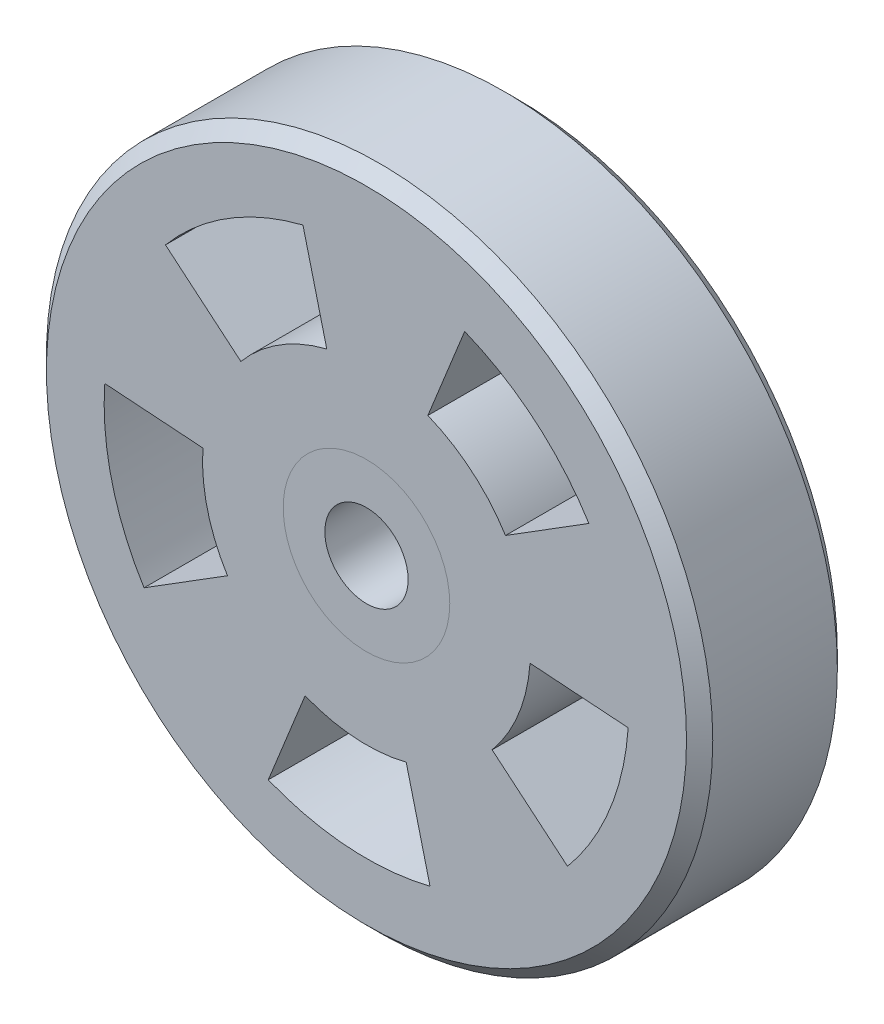
SolidWorks part; units mm, degrees
ref_plane "Front Plane" through (0, 0, 0) normal (0, 0, 1) x (1, 0, 0)
ref_plane "Top Plane" through (0, 0, 0) normal (0, 1, 0) x (1, 0, 0)
ref_plane "Right Plane" through (0, 0, 0) normal (1, 0, 0) x (0, 0, -1)
sketch "Sketch1" plane through (0, 0, 0) normal (0, 0, 1) x (1, 0, 0)
  line L0 (-39.9034, 2.7786) -> (-24.9396, 1.7366)
  line L2 (-9.6882, 38.809) -> (-6.0551, 24.2556)
  line L3 (-21.1973, -13.2542) -> (-33.9157, -21.2066)
  line L4 (-19.1558, 16.0641) -> (-30.6493, 25.7026)
  line L5 (33.9157, 21.2066) -> (21.1973, 13.2542)
  line L6 (9.3584, 23.1823) -> (14.9735, 37.0917)
  line L7 (30.6493, -25.7026) -> (19.1558, -16.0641)
  line L8 (24.9396, -1.7366) -> (39.9034, -2.7786)
  line L9 (-14.9735, -37.0917) -> (-9.3584, -23.1823)
  line L10 (6.0551, -24.2556) -> (9.6882, -38.809)
  circle A0 centre (0, 0) radius 12.7
  circle A2 centre (0, 0) radius 50.8
  circle A3 centre (0, 0) radius 5.0726
  arc A5 (-21.1973, -13.2542) -> (-24.9396, 1.7366) centre (0, 0) cw
  arc A6 (-39.9034, 2.7786) -> (-33.9157, -21.2066) centre (0, 0) ccw
  circle A7 centre (0, 0) radius 50.8
  arc A8 (-19.1558, 16.0641) -> (-6.0551, 24.2556) centre (0, 0) cw
  arc A9 (-9.6882, 38.809) -> (-30.6493, 25.7026) centre (0, 0) ccw
  circle A10 centre (0, 0) radius 50.8
  arc A11 (9.3584, 23.1823) -> (21.1973, 13.2542) centre (0, 0) cw
  arc A12 (33.9157, 21.2066) -> (14.9735, 37.0917) centre (0, 0) ccw
  circle A13 centre (0, 0) radius 50.8
  arc A14 (24.9396, -1.7366) -> (19.1558, -16.0641) centre (0, 0) cw
  arc A15 (30.6493, -25.7026) -> (39.9034, -2.7786) centre (0, 0) ccw
  circle A16 centre (0, 0) radius 50.8
  arc A17 (6.0551, -24.2556) -> (-9.3584, -23.1823) centre (0, 0) cw
  arc A18 (-14.9735, -37.0917) -> (9.6882, -38.809) centre (0, 0) ccw
  point P33 (0, 0)
  dimension "D1" = 101.6
  dimension "D2" = 25.4
  dimension "D3" = 5
extrude "Boss-Extrude1" add sketch "Sketch1" along normal blind 23 contours A2 A18 L9 A17 L10 A15 L7 A14 L8 A12 L5 A11 L6 A9 L2 A8 L4 A6 L0 A5 L3 A0
chamfer "Chamfer1" distance 2 angle 45 2 edges at (50.8, 0, 0) (50.8, 0, 23)
sketch "Sketch3" plane through (0, 0, 23) normal (0, 0, 1) x (1, 0, 0)
  circle A0 centre (0, 0) radius 12.7
  circle A1 centre (0, 0) radius 6.35
  dimension "D1" = 12.7
extrude "Boss-Extrude3" add sketch "Sketch3" against normal up to surface (23 mm away) separate body up to face at (48.8, 0, 0)
equation "\"D2@Sketch1\"=0.25 * \"D1@Sketch1\""
